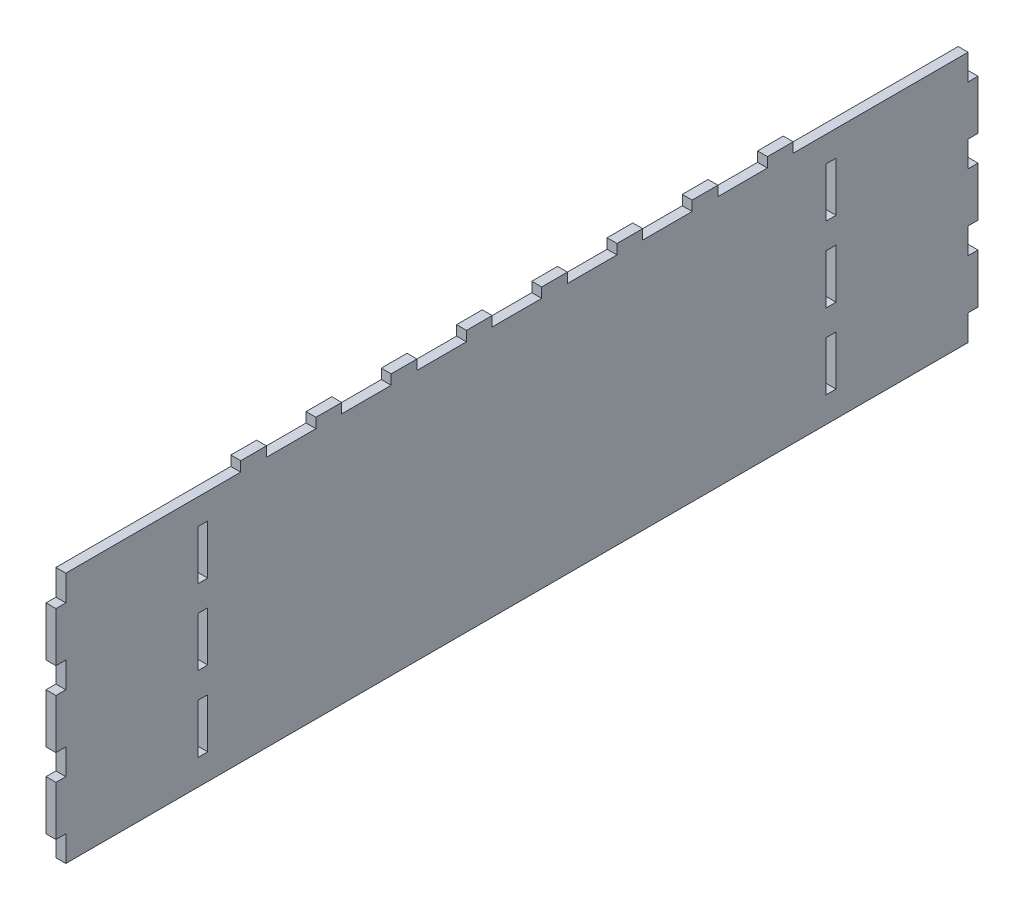
SolidWorks part; units mm, degrees
material "ENPH 253 Hardboard"
ref_plane "Front Plane" through (0, 0, 0) normal (0, 0, 1) x (1, 0, 0)
ref_plane "Top Plane" through (0, 0, 0) normal (0, 1, 0) x (1, 0, 0)
ref_plane "Right Plane" through (0, 0, 0) normal (1, 0, 0) x (0, 0, -1)
sketch "Sketch1" plane through (0, 0, 0) normal (1, 0, 0) x (0, 0, -1)
  line L1 (-139.7, 38.1) -> (139.7, 38.1)
  line L2 (-139.7, 38.1) -> (-139.7, -38.1)
  line L3 (-139.7, -38.1) -> (139.7, -38.1)
  line L4 (139.7, 38.1) -> (139.7, -38.1)
  line L5 (-139.7, 38.1) -> (139.7, -38.1) construction
  line L6 (-139.7, -38.1) -> (139.7, 38.1) construction
  point P0 (0, 0)
  dimension "D1" = 279.4
  dimension "D2" = 76.2
extrude "Boss-Extrude1" add sketch "Sketch1" against normal blind 3 contours L2 L3 L4 L1
sketch "Sketch3" plane through (-3, 0, 0) normal (-1, 0, 0) x (0, 0, 1)
  line L9 (-139.7, 38.1) -> (-136.7, 38.1)
  line L10 (-139.7, 38.1) -> (-139.7, 30.3)
  line L11 (-139.7, 30.3) -> (-136.7, 30.3)
  line L12 (-136.7, 38.1) -> (-136.7, 30.3)
  dimension "D9" = 7.8
  dimension "D10" = 3
extrude "Cut-Extrude1" cut sketch "Sketch3" against normal through all
pattern_linear "LPattern1" count 4 spacing 22.8 along (0, -1, 0) of "Cut-Extrude1"
mirror "Mirror1" about plane through (0, 0, 0) normal (0, 0, 1) of "LPattern1", "Cut-Extrude1"
sketch "Sketch4" plane through (0, 0, 0) normal (1, 0, 0) x (0, 0, -1)
  line L1 (-96.7, 30.3) -> (-93.7, 30.3)
  line L2 (-96.7, 30.3) -> (-96.7, 15.3)
  line L3 (-96.7, 15.3) -> (-93.7, 15.3)
  line L4 (-93.7, 30.3) -> (-93.7, 15.3)
  line L5 (-136.7, 38.1) -> (136.7, 38.1) construction
  line L6 (-136.7, 30.3) -> (-136.7, 38.1) construction
  dimension "D1" = 40
  dimension "D2" = 3
  dimension "D3" = 7.8
  dimension "D4" = 15
extrude "Cut-Extrude2" cut sketch "Sketch4" against normal blind 10
pattern_linear "LPattern2" count 3 spacing 22.8 along (0, -1, 0) of "Cut-Extrude2"
mirror "Mirror2" about plane through (0, 0, 0) normal (0, 0, 1) of "LPattern2", "Cut-Extrude2"
sketch "Sketch5" plane through (0, 38.1, 0) normal (0, 1, 0) x (1, 0, 0)
  line L0 (-3, -136.7) -> (-3, 136.7) construction
  line L1 (-3, -75.9) -> (0, -75.9)
  line L2 (-3, -75.9) -> (-3, -83.7)
  line L3 (-3, -83.7) -> (0, -83.7)
  line L4 (0, -75.9) -> (0, -83.7)
  line L5 (0, -136.7) -> (-3, -136.7) construction
  dimension "D1" = 53
  dimension "D2" = 7.8
  dimension "D3" = 3
extrude "Boss-Extrude2" add sketch "Sketch5" along normal blind 3
pattern_linear "LPattern3" count 8 spacing 22.8 along (0, 0, -1) of "Boss-Extrude2"
